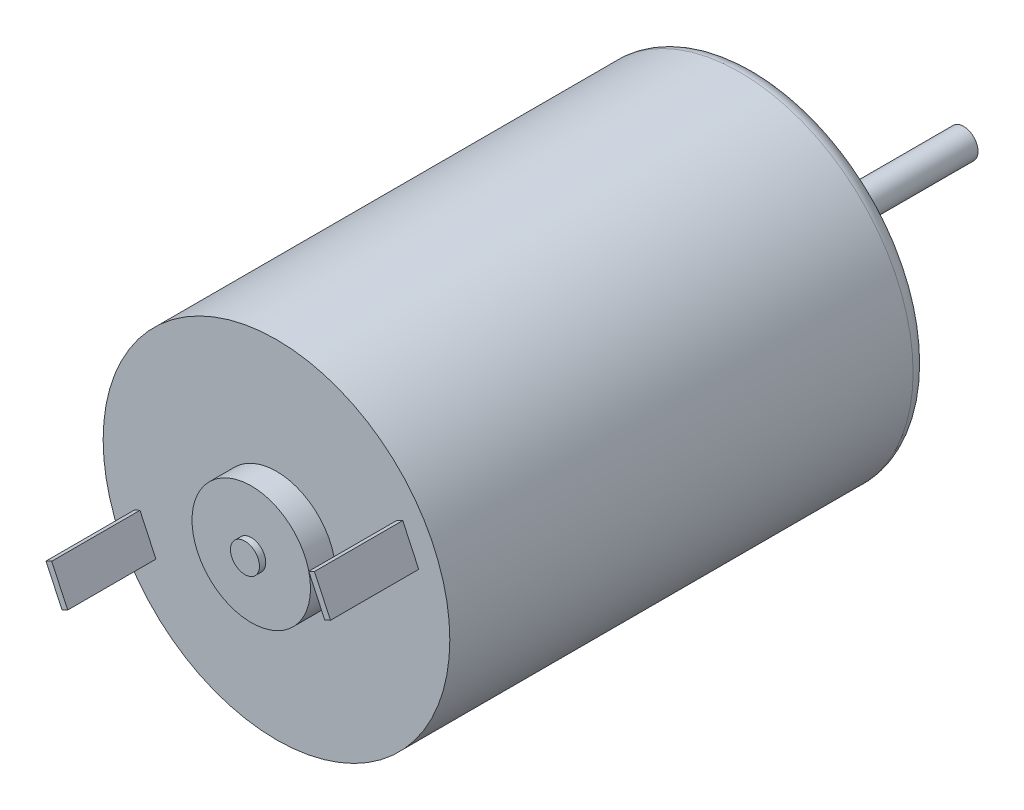
SolidWorks part; units mm, degrees
ref_plane "Front" through (0, 0, 0) normal (0, 0, 1) x (1, 0, 0)
ref_plane "Top" through (0, 0, 0) normal (0, 1, 0) x (1, 0, 0)
ref_plane "Right" through (0, 0, 0) normal (1, 0, 0) x (0, 0, -1)
sketch "Master S" plane through (0, 0, 0) normal (0, 0, 1) x (1, 0, 0)
  line L0 (-6.1459, 12.3) -> (6.1459, 12.3)
  line L1 (0, 12.3) -> (0, -12.3) construction
  line L2 (-6.1459, -12.3) -> (6.1459, -12.3)
  line L3 (0, 0) -> (12.4617, 5.811) construction
  line L4 (11.283, 3.6063) -> (10.0152, 6.3252)
  line L5 (11.283, 3.6063) -> (10.8299, 3.395)
  line L6 (10.0152, 6.3252) -> (9.562, 6.1139)
  line L7 (10.8299, 3.395) -> (9.562, 6.1139)
  line L8 (11.283, 3.6063) -> (9.562, 6.1139) construction
  line L9 (10.0152, 6.3252) -> (10.8299, 3.395) construction
  line L10 (0, 0) -> (5.811, -12.4617) construction
  line L11 (-10.0152, -6.3252) -> (-9.562, -6.1139)
  line L12 (-9.562, -6.1139) -> (-10.8299, -3.395)
  line L13 (-11.283, -3.6063) -> (-10.8299, -3.395)
  line L14 (-10.0152, -6.3252) -> (-11.283, -3.6063)
  line L15 (0, 0) -> (13.75, 0) construction
  line L16 (0, 0) -> (12.4617, -5.811) construction
  line L17 (0, 0) -> (5.811, 12.4617) construction
  circle A0 centre (0, 0) radius 13.75
  circle A1 centre (0, 0) radius 5
  circle A2 centre (0, 0) radius 4.7
  circle A3 centre (0, 0) radius 1.15
  circle A4 centre (7.2505, -3.3809) radius 1
  circle A5 centre (-7.2505, 3.3809) radius 1
  point P14 (10.4225, 4.8601)
  dimension "D1" = 27.5
  dimension "D3" = 10
  dimension "D4" = 9.4
  dimension "D5" = 2.3
  dimension "D11" = 2
  dimension "D2" = 24.6
  dimension "D6" = 65
  dimension "D7" = 0.5
  dimension "D8" = 3
  dimension "D9" = 2.5
  dimension "D10" = 65
  dimension "D12" = 8
sketch "Skizze2" plane through (0, 0, 0) normal (0, 0, 1) x (1, 0, 0)
  line L0 (-6.1459, 12.3) -> (6.1459, 12.3) construction
  line L1 (-6.1459, -12.3) -> (6.1459, -12.3) construction
  line L2 (-6.1459, 12.3) -> (6.1459, 12.3) construction
  line L3 (-6.1459, -12.3) -> (6.1459, -12.3) construction
  circle A0 centre (0, 0) radius 13.75 construction
  arc A1 (-6.1459, 12.3) -> (-6.1459, -12.3) centre (0, 0) ccw construction
  arc A2 (6.1459, -12.3) -> (6.1459, 12.3) centre (0, 0) ccw construction
  circle A3 centre (0, 0) radius 13.75
  dimension "D1" = 27.5
extrude "Aufsatz-Linear austragen1" add sketch "Skizze2" along normal blind 38
sketch "Skizze3" plane through (0, 0, 0) normal (0, 0, -1) x (-1, 0, 0)
  circle A0 centre (0, 0) radius 5 construction
  circle A1 centre (0, 0) radius 5
extrude "Aufsatz-Linear austragen2" add sketch "Skizze3" along normal blind 3.5
sketch "Skizze4" plane through (0, 0, 38) normal (0, 0, 1) x (1, 0, 0)
  circle A0 centre (0, 0) radius 4.7 construction
  circle A1 centre (0, 0) radius 4.7
extrude "Aufsatz-Linear austragen3" add sketch "Skizze4" along normal blind 2
sketch "Skizze5" plane through (0, 0, -3.5) normal (0, 0, -1) x (-1, 0, 0)
  circle A0 centre (0, 0) radius 1.15 construction
  circle A1 centre (0, 0) radius 1.15
extrude "Aufsatz-Linear austragen4" add sketch "Skizze5" along normal blind 13 and the other way offset from surface (44 mm away) 0.5 separate body other way up to face at (4.7, 0, 40)
sketch "Skizze6" plane through (0, 0, 0) normal (0, 0, -1) x (-1, 0, 0)
  circle A0 centre (7.2505, 3.3809) radius 1 construction
  circle A1 centre (-7.2505, -3.3809) radius 1 construction
  circle A2 centre (7.2505, 3.3809) radius 1
  circle A3 centre (-7.2505, -3.3809) radius 1
extrude "Schnitt-Linear austragen1" cut sketch "Skizze6" against normal blind 2
sketch "Skizze7" plane through (0, 0, 38) normal (0, 0, 1) x (1, 0, 0)
  line L0 (11.283, 3.6063) -> (10.8299, 3.395) construction
  line L1 (10.8299, 3.395) -> (9.562, 6.1139) construction
  line L2 (10.0152, 6.3252) -> (9.562, 6.1139) construction
  line L3 (11.283, 3.6063) -> (10.0152, 6.3252) construction
  line L4 (11.283, 3.6063) -> (10.8299, 3.395)
  line L5 (10.8299, 3.395) -> (9.562, 6.1139)
  line L6 (10.0152, 6.3252) -> (9.562, 6.1139)
  line L7 (11.283, 3.6063) -> (10.0152, 6.3252)
  line L8 (-10.0152, -6.3252) -> (-9.562, -6.1139) construction
  line L9 (-9.562, -6.1139) -> (-10.8299, -3.395) construction
  line L10 (-11.283, -3.6063) -> (-10.8299, -3.395) construction
  line L11 (-10.0152, -6.3252) -> (-11.283, -3.6063) construction
  line L12 (-10.0152, -6.3252) -> (-9.562, -6.1139)
  line L13 (-9.562, -6.1139) -> (-10.8299, -3.395)
  line L14 (-11.283, -3.6063) -> (-10.8299, -3.395)
  line L15 (-10.0152, -6.3252) -> (-11.283, -3.6063)
extrude "Aufsatz-Linear austragen5" add sketch "Skizze7" along normal blind 7 separate body
fillet "Verrundung1" radius 1.25 1 edges at (13.75, 0, 0)
sketch "Skizze8" plane through (0, 0, 0) normal (1, 0, 0) x (0, 0, -1)
  line L0 (-26, 19.0597) -> (-26, -19.0597)
  line L1 (0, 0) -> (-26, 0) construction
  dimension "D1" = 26
split line "Trennlinie1" [suppressed]
